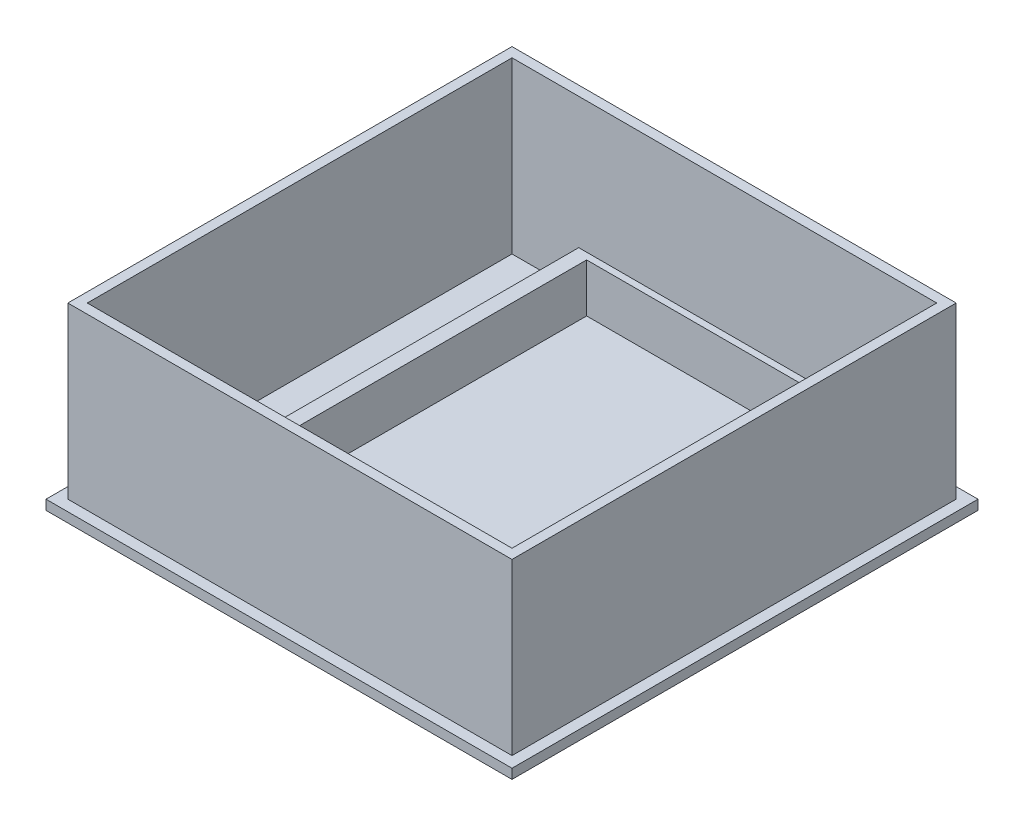
SolidWorks part; units mm, degrees
ref_plane "Front Plane" through (0, 0, 0) normal (0, 0, 1) x (1, 0, 0)
ref_plane "Top Plane" through (0, 0, 0) normal (0, 1, 0) x (1, 0, 0)
ref_plane "Right Plane" through (0, 0, 0) normal (1, 0, 0) x (0, 0, -1)
sketch "Sketch1" plane through (0, 0, 0) normal (0, 1, 0) x (1, 0, 0)
  line L1 (-50, -50) -> (50, -50)
  line L2 (-50, -50) -> (-50, 50)
  line L3 (-50, 50) -> (50, 50)
  line L4 (50, -50) -> (50, 50)
  line L5 (-50, -50) -> (50, 50) construction
  line L6 (-50, 50) -> (50, -50) construction
  point P0 (0, 0)
  dimension "D1" = 100
extrude "Boss-Extrude1" add sketch "Sketch1" along normal blind 4
sketch "Sketch2" plane through (0, 4, 0) normal (0, 1, 0) x (1, 0, 0)
  line L4 (41.75, -41.75) -> (41.75, 41.75)
  line L5 (41.75, 41.75) -> (-41.75, 41.75)
  line L6 (-41.75, 41.75) -> (-41.75, -41.75)
  line L7 (-41.75, -41.75) -> (41.75, -41.75)
  line L8 (45.75, -45.75) -> (45.75, 45.75)
  line L9 (45.75, 45.75) -> (-45.75, 45.75)
  line L10 (-45.75, 45.75) -> (-45.75, -45.75)
  line L11 (-45.75, -45.75) -> (45.75, -45.75)
  line L12 (45.75, -45.75) -> (45.75, 45.75)
  line L13 (45.75, 45.75) -> (-45.75, 45.75)
  line L14 (-45.75, 45.75) -> (-45.75, -45.75)
  line L15 (-45.75, -45.75) -> (45.75, -45.75)
  dimension "D1" = 4.25
  dimension "D2" = 4
extrude "Boss-Extrude2" add sketch "Sketch2" along normal blind 35
sketch "Sketch3" plane through (0, 0, -45.75) normal (0, 0, -1) x (-1, 0, 0)
  line L0 (-50, 4) -> (50, 4) construction
  line L1 (-2, 8) -> (2, 8)
  line L2 (-2, 8) -> (-2, 4)
  line L3 (-2, 4) -> (2, 4)
  line L4 (2, 8) -> (2, 4)
  line L5 (-2, 8) -> (2, 4) construction
  line L6 (-2, 4) -> (2, 8) construction
  point P0 (0, 6)
  dimension "D1" = 4
extrude "Cut-Extrude1" cut sketch "Sketch3" against normal up to surface (4 mm away) up to face at (0, 21.5, -41.75)
sketch "Sketch4" plane through (0, 4, 0) normal (0, 1, 0) x (1, 0, 0)
  line L0 (41.75, 41.75) -> (-41.75, 41.75) construction
  line L1 (-25, -39) -> (25, -39)
  line L2 (-25, -39) -> (-25, 39)
  line L3 (-25, 39) -> (25, 39)
  line L4 (25, -39) -> (25, 39)
  line L5 (-25, -39) -> (25, 39) construction
  line L6 (-25, 39) -> (25, -39) construction
  line L7 (-13, 22.21) -> (-28, 22.21)
  line L8 (-13, 22.21) -> (-13, 41.75)
  line L9 (-13, 41.75) -> (-28, 41.75)
  line L10 (-28, 22.21) -> (-28, 41.75)
  line L11 (-13, 22.21) -> (-28, 41.75) construction
  line L12 (-13, 41.75) -> (-28, 22.21) construction
  line L13 (-41.75, -41.75) -> (41.75, -41.75) construction
  line L14 (13, 22.21) -> (28, 22.21)
  line L15 (13, 22.21) -> (13, 41.75)
  line L16 (13, 41.75) -> (28, 41.75)
  line L17 (28, 22.21) -> (28, 41.75)
  line L18 (13, 22.21) -> (28, 41.75) construction
  line L19 (13, 41.75) -> (28, 22.21) construction
  line L20 (-28, -22.21) -> (-13, -22.21)
  line L21 (-28, -22.21) -> (-28, -41.75)
  line L22 (-28, -41.75) -> (-13, -41.75)
  line L23 (-13, -22.21) -> (-13, -41.75)
  line L24 (-28, -22.21) -> (-13, -41.75) construction
  line L25 (-28, -41.75) -> (-13, -22.21) construction
  line L27 (28, -22.21) -> (13, -22.21)
  line L28 (28, -22.21) -> (28, -41.75)
  line L29 (28, -41.75) -> (13, -41.75)
  line L30 (13, -22.21) -> (13, -41.75)
  line L31 (28, -22.21) -> (13, -41.75) construction
  line L32 (28, -41.75) -> (13, -22.21) construction
  line L33 (-13, 41.75) -> (13, 41.75)
  line L34 (-13, 41.75) -> (-13, 39)
  line L35 (-13, 39) -> (13, 39)
  line L36 (13, 41.75) -> (13, 39)
  line L37 (-28, 22.21) -> (-25, 22.21)
  line L38 (-28, 22.21) -> (-28, -22.21)
  line L39 (-28, -22.21) -> (-25, -22.21)
  line L40 (-25, 22.21) -> (-25, -22.21)
  line L41 (28, 22.21) -> (25, 22.21)
  line L42 (28, 22.21) -> (28, -22.21)
  line L43 (28, -22.21) -> (25, -22.21)
  line L44 (25, 22.21) -> (25, -22.21)
  line L45 (-13, -41.75) -> (13, -41.75)
  line L46 (-13, -41.75) -> (-13, -39)
  line L47 (-13, -39) -> (13, -39)
  line L48 (13, -41.75) -> (13, -39)
  point P0 (0, 0)
  point P6 (-20.5, 31.98)
  point P13 (20.5, 31.98)
  point P18 (-20.5, -31.98)
  point P25 (20.5, -31.98)
  line M17 (-41.75, -41.75) -> (41.75, -41.75)
  line M19 (41.75, 41.75) -> (2, 41.75)
  line M27 (-2, 41.75) -> (-41.75, 41.75)
  dimension "D1" = 78
  dimension "D2" = 50
  dimension "D3" = 3
  dimension "D4" = 15
extrude "Boss-Extrude3" add sketch "Sketch4" along normal blind 10 contours L10 L7 L2 L3 L8 M27 | L14 L17 L15 L3 L4 M19 | L1 L30 L28 L27 L4 M17 | L23 L1 L2 L20 L21 M17 | L46 L45 L48 L47 | L38 L37 L40 L39 | L34 L33 L36 L35 | L42 L41 L44 L43
sketch "Sketch5" plane through (0, 4, 0) normal (0, 1, 0) x (1, 0, 0)
  line L1 (-25, 39) -> (25, 39)
  line L2 (-25, 39) -> (-25, 40.375)
  line L3 (-25, 40.375) -> (25, 40.375)
  line L4 (25, 39) -> (25, 40.375)
  dimension "D1" = 1.375
extrude "Cut-Extrude2" cut sketch "Sketch5" along normal through all
sketch "Sketch6" plane through (0, 0, -45.75) normal (0, 0, -1) x (-1, 0, 0)
  line L0 (-45.75, 4) -> (-2, 4) construction
  line L1 (-4, 19.5) -> (4, 19.5)
  line L2 (-4, 19.5) -> (-4, 27.5)
  line L3 (-4, 27.5) -> (4, 27.5)
  line L4 (4, 19.5) -> (4, 27.5)
  line L5 (-4, 19.5) -> (4, 27.5) construction
  line L6 (-4, 27.5) -> (4, 19.5) construction
  point P0 (0, 23.5)
  dimension "D1" = 15.5
  dimension "D2" = 8
  dimension "D3" = 0
  dimension "D4" = 8
extrude "Cut-Extrude4" [suppressed] cut sketch "Sketch6" against normal blind 12
sketch "Sketch7" plane through (0, 0, -45.75) normal (0, 0, -1) x (-1, 0, 0)
  line L1 (-2, 8) -> (2, 8)
  line L2 (-2, 8) -> (-2, 4)
  line L3 (-2, 4) -> (2, 4)
  line L4 (2, 8) -> (2, 4)
extrude "Boss-Extrude5" add sketch "Sketch7" against normal blind 4
sketch "Sketch8" plane through (0, 39, 0) normal (0, 1, 0) x (1, 0, 0)
  line L0 (45.75, 45.75) -> (-45.75, 45.75) construction
  line L1 (-43.7452, 43.75) -> (43.75, 43.75)
  line L2 (-43.7452, 43.75) -> (-43.7452, -43.75)
  line L3 (-43.7452, -43.75) -> (43.75, -43.75)
  line L4 (43.75, 43.75) -> (43.75, -43.75)
  line L5 (45.75, -45.75) -> (45.75, 45.75) construction
  line L6 (-45.75, -45.75) -> (45.75, -45.75) construction
  line L7 (-45.75, 45.75) -> (-45.75, -45.75) construction
  dimension "D1" = 2
  dimension "D2" = 2
  dimension "D3" = 2
  dimension "D4" = 2.0048
extrude "Cut-Extrude6" cut sketch "Sketch8" against normal up to surface (25 mm away) up to face at (0, 14, 0)
sketch "Sketch10" plane through (0, 14, 0) normal (0, 1, 0) x (1, 0, 0)
  line L1 (-43.7452, 43.75) -> (43.75, 43.75)
  line L2 (-43.7452, 43.75) -> (-43.7452, -43.75)
  line L3 (-43.7452, -43.75) -> (43.75, -43.75)
  line L4 (43.75, 43.75) -> (43.75, -43.75)
  line L5 (-41.75, 41.75) -> (41.75, 41.75)
  line L6 (-41.75, 41.75) -> (-41.75, -41.75)
  line L7 (-41.75, -41.75) -> (41.75, -41.75)
  line L8 (41.75, 41.75) -> (41.75, -41.75)
extrude "Cut-Extrude8" cut sketch "Sketch10" against normal up to surface (10 mm away) contours L2 L1 L4 L3 | L6 L5 L8 L7 up to face at (0, 4, -0.6875)
sketch "Sketch11" plane through (0, 4, 0) normal (0, 1, 0) x (1, 0, 0)
  line L0 (-50, 50) -> (-50, -50) construction
  line L1 (-48, 48) -> (48, 48)
  line L2 (-48, 48) -> (-48, -48)
  line L3 (-48, -48) -> (48, -48)
  line L4 (48, 48) -> (48, -48)
  line L5 (50, 50) -> (-50, 50) construction
  line L6 (50, -50) -> (50, 50) construction
  line L7 (-50, -50) -> (50, -50) construction
  dimension "D1" = 2
  dimension "D2" = 2
  dimension "D3" = 2
  dimension "D4" = 2
extrude "Cut-Extrude9" cut sketch "Sketch11" against normal blind 32 flip side to cut
sketch "Sketch12" plane through (0, 0, -48) normal (0, 0, -1) x (-1, 0, 0)
  line L0 (48, 0) -> (48, 4) construction
  line L1 (-48, 0) -> (48, 0)
  line L2 (-48, 0) -> (-48, 2)
  line L3 (-48, 2) -> (48, 2)
  line L4 (48, 0) -> (48, 2)
extrude "Cut-Extrude10" cut sketch "Sketch12" against normal through all
